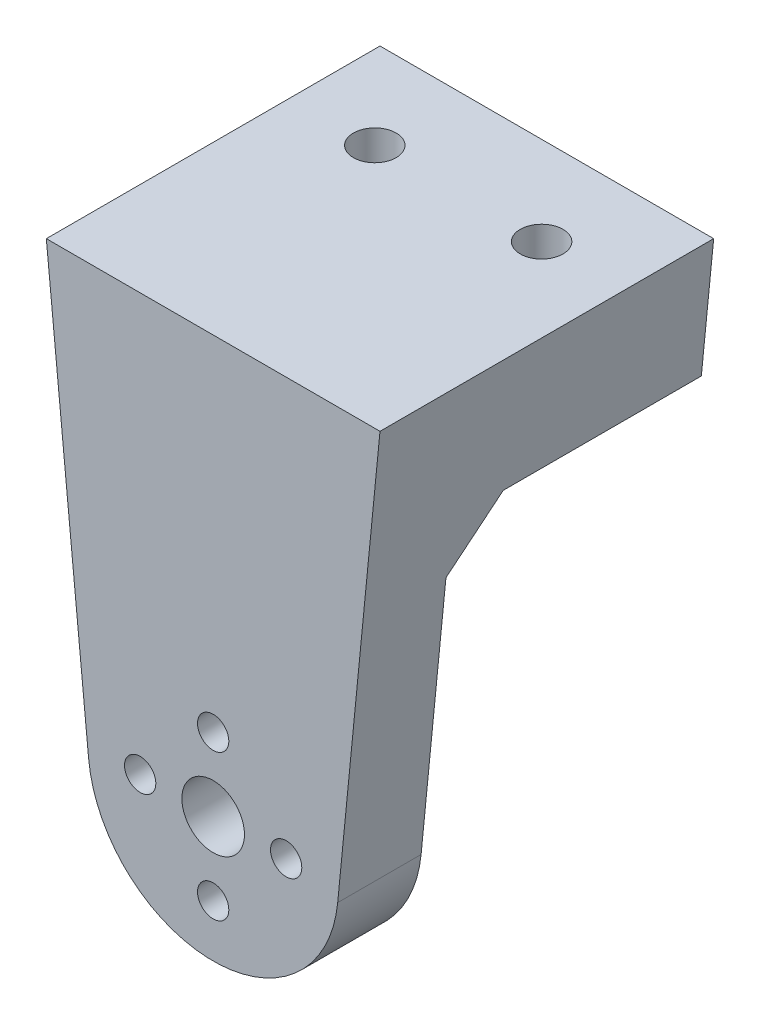
SolidWorks part; units mm, degrees
ref_plane "Front" through (0, 0, 0) normal (0, 0, 1) x (1, 0, 0)
ref_plane "Top" through (0, 0, 0) normal (0, 1, 0) x (1, 0, 0)
ref_plane "Right" through (0, 0, 0) normal (1, 0, 0) x (0, 0, -1)
sketch "Sketch1" plane through (0, 0, 0) normal (0, 0, 1) x (1, 0, 0)
  line L0 (-11.9422, -1.1769) -> (-16, 40)
  line L1 (-16, 40) -> (16, 40)
  line L2 (16, 40) -> (11.9422, -1.1769)
  line L3 (0, 40) -> (0, 0) construction
  circle A0 centre (0, 0) radius 12
  circle A1 centre (0, 7) radius 1.5
  circle A2 centre (7, 0) radius 1.5
  circle A3 centre (0, -7) radius 1.5
  circle A4 centre (-7, 0) radius 1.5
  point P10 (8.2027, -2.3592)
  point P11 (0, 0)
  point P19 (0, 0)
  dimension "D1" = 24
  dimension "D4" = 3
  dimension "D2" = 32
  dimension "D3" = 40
  dimension "D5" = 7
  dimension "D6" = 4
extrude "Boss-Extrude1" add sketch "Sketch1" along normal blind 8
sketch "Sketch3" plane through (0, 0, 0) normal (0, 0, -1) x (-1, 0, 0)
  line L3 (14.8174, 28) -> (-14.8174, 28)
  line L4 (16, 28) -> (-16, 28) construction
  line L6 (11.9422, -1.1769) -> (16, 40)
  line L7 (16, 40) -> (-16, 40)
  line L8 (-16, 40) -> (-11.9422, -1.1769)
  line L9 (14.8174, 28) -> (16, 40)
  line L10 (16, 40) -> (-16, 40)
  line L11 (-16, 40) -> (-14.8174, 28)
  arc A2 (-11.9422, -1.1769) -> (11.9422, -1.1769) centre (0, 0) ccw
  dimension "D1" = 0
  dimension "D2" = 12
extrude "Boss-Extrude2" add sketch "Sketch3" along normal blind 24
chamfer "Chamfer1" distance 5 angle 45 1 edges at (0, 28, 0)
sketch "Sketch5" plane through (0, 0, 0) normal (0, 0, -1) x (-1, 0, 0)
  circle A0 centre (0, 0) radius 3
  dimension "D1" = 6
extrude "Cut-Extrude2" cut sketch "Sketch5" against normal up to next
sketch "Sketch6" plane through (0, 40, 0) normal (0, -1, 0) x (1, 0, 0)
  line L14 (14.8174, -24) -> (-14.8174, -24) construction
  circle A2 centre (-8, -15.5) radius 2.05
  circle A3 centre (8, -15.5) radius 2.05
  point P22 (-8.0775, -15.8271)
  dimension "D5" = 4.1
  dimension "D6" = 4.1
  dimension "D1" = 16
  dimension "D2" = 8
  dimension "D7" = 8.5
extrude "Cut-Extrude6" cut sketch "Sketch6" along normal blind 5 contours A2 | A3
